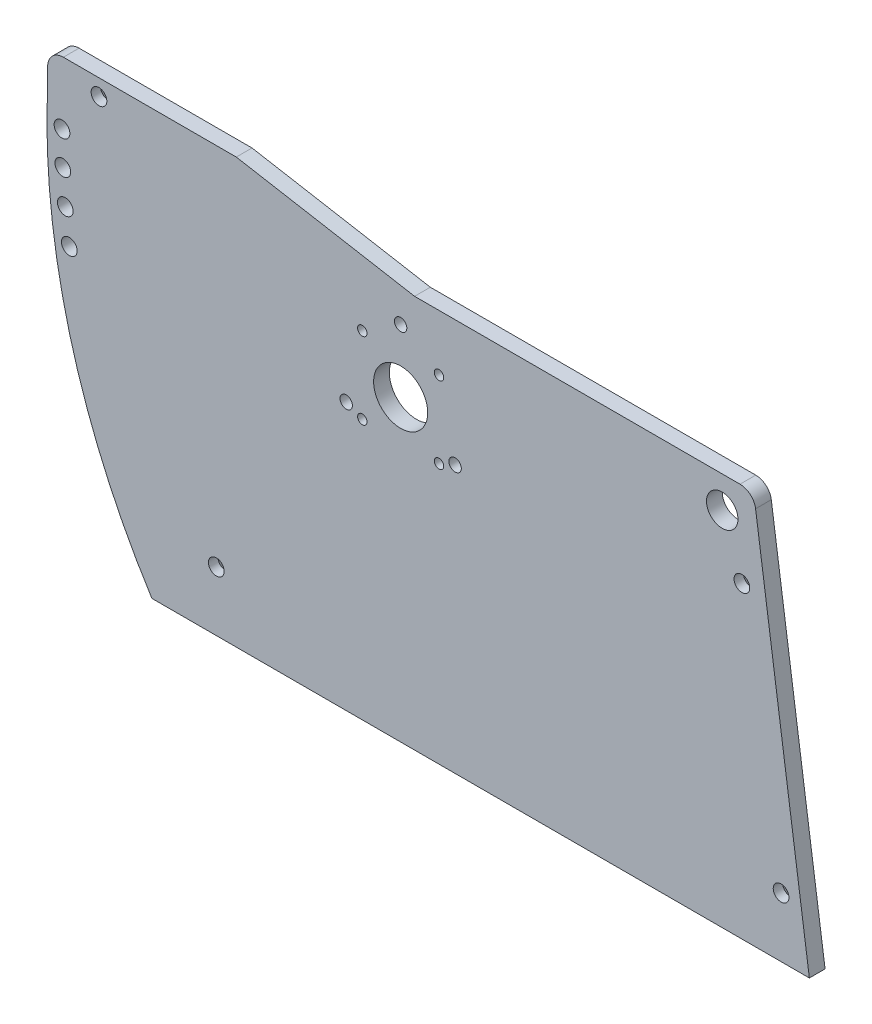
SolidWorks part; units mm, degrees
ref_plane "Front Plane" through (0, 0, 0) normal (0, 0, 1) x (1, 0, 0)
ref_plane "Top Plane" through (0, 0, 0) normal (0, 1, 0) x (1, 0, 0)
ref_plane "Right Plane" through (0, 0, 0) normal (1, 0, 0) x (0, 0, -1)
sketch "Sketch18" plane through (0, 0, 0) normal (0, 0, 1) x (1, 0, 0)
  line L0 (0, 0) -> (-265.6047, 0)
  line L4 (0, 0) -> (-21.7272, 153.2911)
  line L5 (-28.0144, 158.75) -> (-159.4738, 158.75)
  line L6 (-159.4738, 158.75) -> (-231.4991, 171.45)
  line L7 (-231.4991, 171.45) -> (-301.3491, 171.45)
  line L8 (-307.6991, 165.1) -> (-307.6991, 158.75)
  circle A0 centre (-180.594, 136.144) radius 1.905
  arc A1 (-307.6991, 158.75) -> (-265.6047, 0) centre (-35.2009, 146.05) ccw
  arc A2 (-21.7272, 153.2911) -> (-28.0144, 158.75) centre (-28.0144, 152.4) ccw
  arc A3 (-301.3491, 171.45) -> (-307.6991, 165.1) centre (-301.3491, 165.1) ccw
  circle A4 centre (-11.4235, 24.0347) radius 3.175
  circle A5 centre (-27.2534, 124.4065) radius 3.175
  circle A6 centre (-35.2009, 146.05) radius 6.35
  circle A7 centre (-301.9009, 146.05) radius 3.175
  circle A8 centre (-301.5697, 132.7614) radius 3.175
  circle A9 centre (-300.5799, 119.5375) radius 3.175
  circle A10 centre (-298.9435, 106.4428) radius 3.175
  circle A11 centre (-239.5689, 24.0347) radius 3.175
  circle A12 centre (-286.9621, 164.8507) radius 3.175
  circle A13 centre (-187.097, 107.95) radius 2.5
  circle A14 centre (-180.594, 105.156) radius 1.905
  circle A15 centre (-165.1, 120.65) radius 10.922
  circle A16 centre (-165.1, 146.05) radius 2.5
  circle A17 centre (-149.606, 105.156) radius 1.905
  circle A18 centre (-149.606, 136.144) radius 1.905
  circle A19 centre (-143.103, 107.95) radius 2.5
  circle A20 centre (-35.2009, 146.05) radius 266.7 construction
  dimension "D7" = 13.2886
  dimension "D8" = 13.2239
  dimension "D9" = 13.0947
  dimension "D11" = 6.35
  dimension "D12" = 20.7369
  dimension "D16" = 6.35
  dimension "D17" = 6.35
  dimension "D19" = 43.9941
  dimension "D20" = 21.997
  dimension "D21" = 15.494
  dimension "D22" = 15.494
  dimension "D23" = 30.988
  dimension "D24" = 30.988
  dimension "D25" = 30.988
  dimension "D26" = 15.494
  dimension "D2" = 158.75
  dimension "D3" = 81.933
  dimension "D4" = 12.7
  dimension "D6" = 25.4
  dimension "D13" = 6.5993
  dimension "D14" = 76.2
  dimension "D15" = 72.0253
extrude "Boss-Extrude4" add sketch "Sketch18" along normal blind 6.35 separate body
chamfer "Chamfer1" distance 2.54 angle 45 4 edges at (-24.0784, 124.4065, 0) (-8.2485, 24.0347, 0) (-236.3939, 24.0347, 0) (-283.7871, 164.8507, 0)
